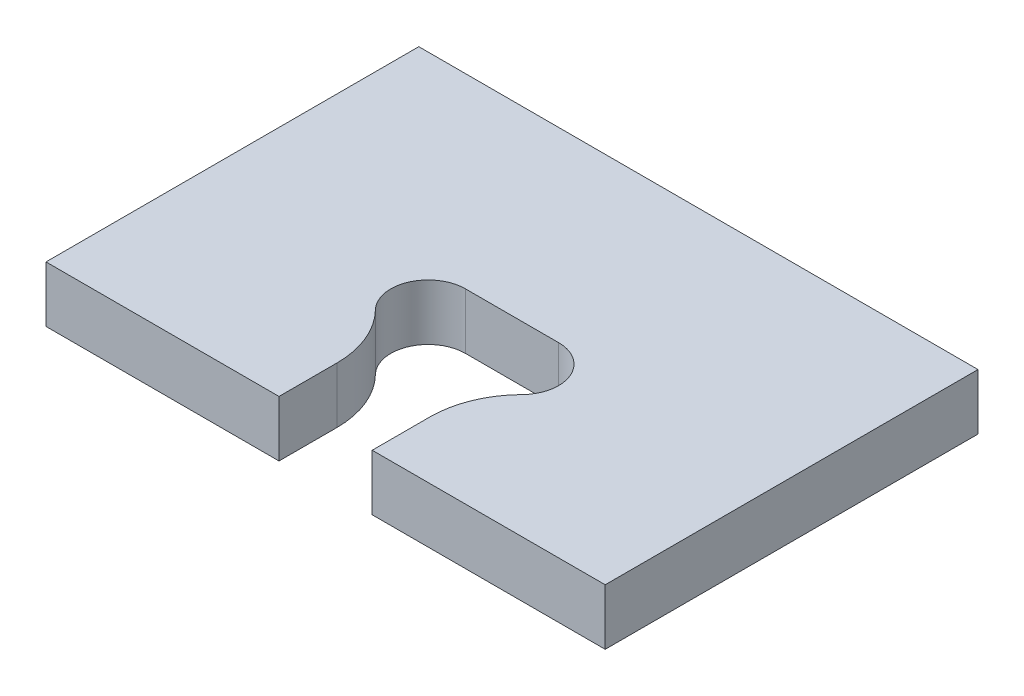
SolidWorks part; units mm, degrees
ref_plane "Front" through (0, 0, 0) normal (0, 0, 1) x (1, 0, 0)
ref_plane "Top" through (0, 0, 0) normal (0, 1, 0) x (1, 0, 0)
ref_plane "Right" through (0, 0, 0) normal (1, 0, 0) x (0, 0, -1)
sketch "Sketch1" plane through (0, 0, 0) normal (0, 1, 0) x (1, 0, 0)
  line L0 (-2.5, 0) -> (-2.5, 3.101)
  line L1 (-15, 20) -> (15, 20)
  line L2 (-15, 20) -> (-15, 0)
  line L3 (-15, 0) -> (-2.5, 0)
  line L4 (15, 20) -> (15, 0)
  line L5 (-2.5, 10) -> (2.5, 10)
  line L6 (2.5, 3.101) -> (2.5, 0)
  line L7 (2.5, 0) -> (15, 0)
  line L8 (-2.5, 0) -> (2.5, 0) construction
  arc A0 (-3.9286, 6.6003) -> (-2.5, 10) centre (-2.5, 8) cw
  arc A1 (2.5, 10) -> (3.9286, 6.6003) centre (2.5, 8) cw
  arc A2 (3.9286, 6.6003) -> (2.5, 3.101) centre (7.5, 3.101) ccw
  arc A3 (-2.5, 3.101) -> (-3.9286, 6.6003) centre (-7.5, 3.101) ccw
  point P16 (-2.641, 3.101)
  dimension "D3" = 5
  dimension "D4" = 2
  dimension "D1" = 20
  dimension "D2" = 30
  dimension "D5" = 10
  dimension "D6" = 5
extrude "Boss-Extrude1" add sketch "Sketch1" along normal blind 3
